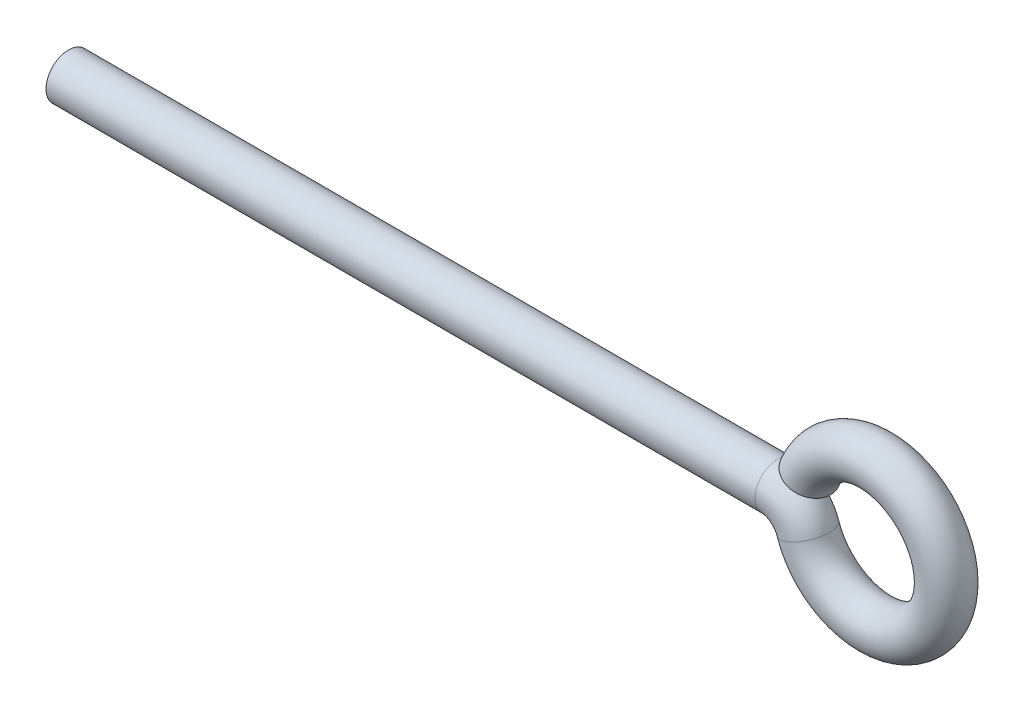
SolidWorks part; units mm, degrees
material "AISI 1020"
ref_plane "Front Plane" through (0, 0, 0) normal (0, 0, 1) x (1, 0, 0)
ref_plane "Top Plane" through (0, 0, 0) normal (0, 1, 0) x (1, 0, 0)
ref_plane "Right Plane" through (0, 0, 0) normal (1, 0, 0) x (0, 0, -1)
sketch "Sketch1" plane through (0, 0, 0) normal (0, 0, 1) x (1, 0, 0)
  line L0 (0, 0) -> (100, 0)
  line L1 (104.5398, 3.7704) -> (102.6546, -0.8606) construction
  arc A0 (100, 0) -> (104.2993, -3.1151) centre (100, -4.5245) cw
  arc A1 (104.2993, -3.1151) -> (104.5398, 3.7704) centre (113.8018, 0) ccw
  point P7 (102.6546, -0.8606)
  point P8 (76.8123, 3.171)
  dimension "D1" = 10
  dimension "D2" = 5
  dimension "D3" = 100
sweep "Sweep2" add path "Sketch1" circular profile diameter 6.35 parameters "D3"=6.35
